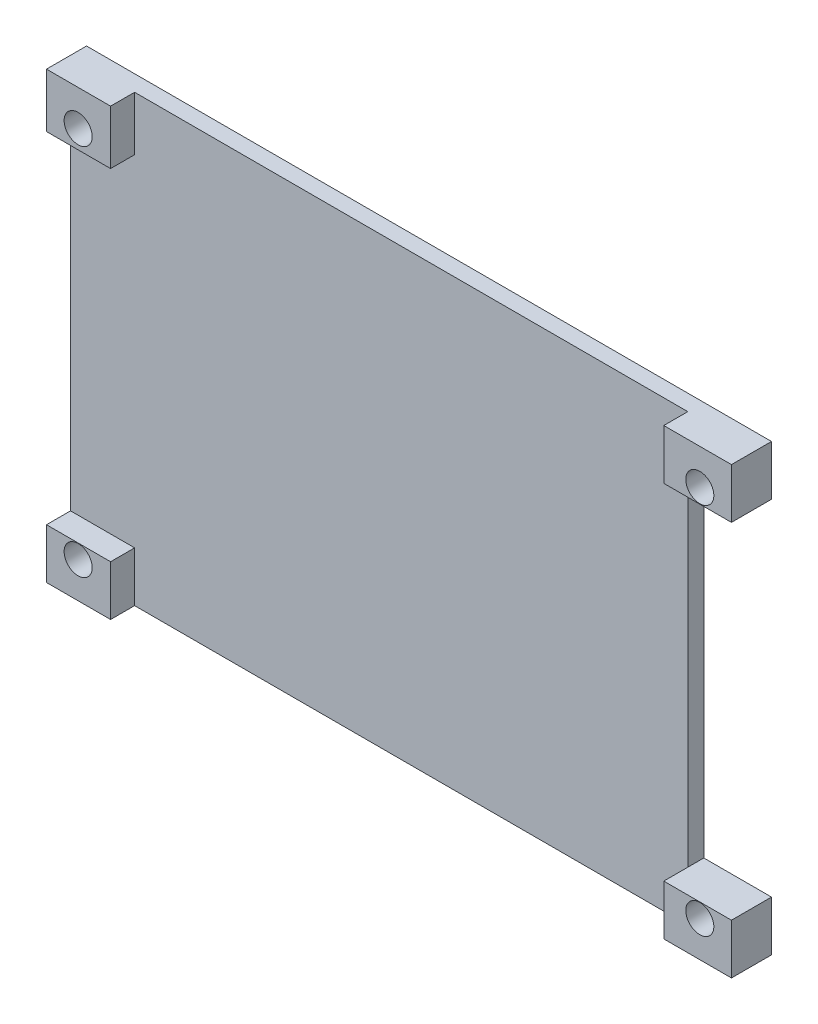
SolidWorks part; units mm, degrees
ref_plane "前视基准面" through (0, 0, 0) normal (0, 0, 1) x (1, 0, 0)
ref_plane "上视基准面" through (0, 0, 0) normal (0, 1, 0) x (1, 0, 0)
ref_plane "右视基准面" through (0, 0, 0) normal (1, 0, 0) x (0, 0, -1)
sketch "草图1" plane through (0, 0, 0) normal (0, 0, 1) x (1, 0, 0)
  line L0 (85.5, 49.25) -> (77.05, 49.25)
  line L1 (0, 0) -> (85.5, 0)
  line L2 (0, 0) -> (0, 55.5)
  line L3 (0, 55.5) -> (85.5, 55.5)
  line L4 (85.5, 0) -> (85.5, 6.25)
  line L9 (77.05, 49.25) -> (77.05, 6.25)
  line L10 (77.05, 6.25) -> (85.5, 6.25)
  line L11 (85.5, 49.25) -> (85.5, 55.5)
  circle A0 centre (3.95, 51.05) radius 1.75
  circle A1 centre (81.55, 51.05) radius 1.75
  circle A2 centre (3.95, 4.45) radius 1.75
  circle A3 centre (81.55, 4.45) radius 1.75
  point P13 (0, 27.75)
  point P14 (42.75, 55.5)
  point P17 (77.05, 27.75)
  dimension "D7" = 3.5
  dimension "D1" = 85.5
  dimension "D2" = 55.5
  dimension "D3" = 77.6
  dimension "D4" = 46.6
  dimension "D5" = 23.3
  dimension "D6" = 38.8
  dimension "D8" = 4.5
  dimension "D9" = 43
extrude "凸台-拉伸1" add sketch "草图1" along normal blind 2
sketch "草图3" plane through (0, 0, 2) normal (0, 0, 1) x (1, 0, 0)
  line L1 (0, 55.5) -> (8, 55.5)
  line L2 (0, 55.5) -> (0, 48.75)
  line L3 (0, 48.75) -> (8, 48.75)
  line L4 (8, 55.5) -> (8, 48.75)
  line L5 (0, 0) -> (8, 0)
  line L6 (0, 0) -> (0, 6.25)
  line L7 (0, 6.25) -> (8, 6.25)
  line L8 (8, 0) -> (8, 6.25)
  line L9 (77.05, 49.25) -> (85.5, 49.25)
  line L10 (77.05, 49.25) -> (77.05, 55.5)
  line L11 (77.05, 55.5) -> (85.5, 55.5)
  line L12 (85.5, 49.25) -> (85.5, 55.5)
  line L13 (77.05, 6.25) -> (85.5, 6.25)
  line L14 (77.05, 6.25) -> (77.05, 0)
  line L15 (77.05, 0) -> (85.5, 0)
  line L16 (85.5, 6.25) -> (85.5, 0)
  circle A0 centre (3.95, 4.45) radius 1.75 construction
  circle A1 centre (81.55, 4.45) radius 1.75 construction
  circle A2 centre (81.55, 51.05) radius 1.75 construction
  circle A3 centre (3.95, 51.05) radius 1.75 construction
  circle A4 centre (3.95, 4.45) radius 1.75
  circle A5 centre (81.55, 4.45) radius 1.75
  circle A6 centre (81.55, 51.05) radius 1.75
  circle A7 centre (3.95, 51.05) radius 1.75
  dimension "D1" = 8
  dimension "D2" = 6.75
extrude "凸台-拉伸2" add sketch "草图3" along normal blind 3
